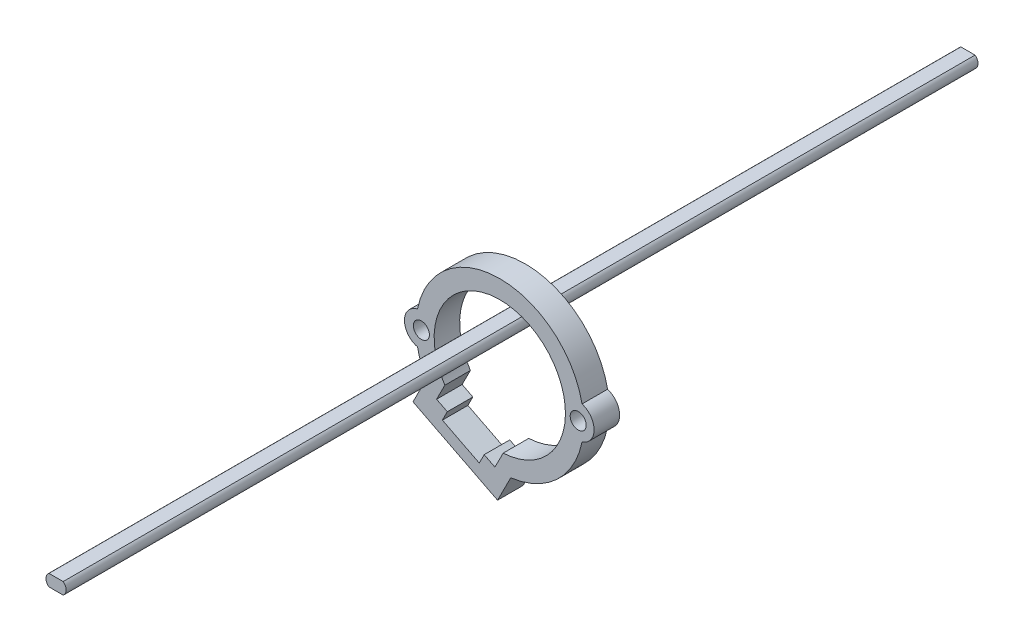
SolidWorks part; units mm, degrees
ref_plane "Front Plane" through (0, 0, 0) normal (0, 0, 1) x (1, 0, 0)
ref_plane "Top Plane" through (0, 0, 0) normal (0, 1, 0) x (1, 0, 0)
ref_plane "Right Plane" through (0, 0, 0) normal (1, 0, 0) x (0, 0, -1)
sketch "Sketch1" plane through (0, 0, 0) normal (0, 0, 1) x (1, 0, 0)
  circle A0 centre (0, 0) radius 23
  circle A1 centre (0, 0) radius 18
  dimension "D1" = 36
  dimension "D2" = 5
extrude "Boss-Extrude1" add sketch "Sketch1" along normal blind 7
sketch "Sketch3" plane through (0, 0, 0) normal (0, 0, 1) x (1, 0, 0)
  line L0 (-23.8014, -18.1679) -> (-0.6174, -29.9366)
  line L1 (-0.6174, -29.9366) -> (3.0037, -22.803)
  line L2 (-23.8014, -18.1679) -> (-20.1803, -11.0343)
  circle A0 centre (0, 0) radius 23 construction
  arc A2 (-20.1803, -11.0343) -> (3.0037, -22.803) centre (0, 0) ccw
  dimension "D1" = 26
  dimension "D2" = 8
  dimension "D3" = 8
extrude "Boss-Extrude2" add sketch "Sketch3" along normal blind 7
sketch "Sketch5" plane through (0, 0, 0) normal (0, 0, 1) x (1, 0, 0)
  line L0 (-15.0623, -9.8553) -> (-17.3255, -14.3138)
  line L1 (-17.3255, -14.3138) -> (-1.3285, -22.4342)
  line L2 (-1.3285, -22.4342) -> (0.9347, -17.9757)
  line L4 (-23.8014, -18.1679) -> (-0.6174, -29.9366) construction
  circle A0 centre (0, 0) radius 18 construction
  arc A1 (0.9347, -17.9757) -> (-15.0623, -9.8553) centre (0, 0) cw
  dimension "D1" = 17.94
  dimension "D2" = 5
  dimension "D3" = 5
extrude "Cut-Extrude1" cut sketch "Sketch5" along normal blind 7
sketch "Sketch6" plane through (0, 0, 0) normal (0, 0, 1) x (1, 0, 0)
  arc A0 (-22.5555, -4.5) -> (-22.5555, 4.5) centre (-21.5191, 0) cw
  circle A1 centre (0, 0) radius 23 construction
  arc A2 (22.5555, -4.5) -> (22.5555, 4.5) centre (21.1441, 0) ccw
  arc A3 (-22.5555, -4.5) -> (-22.5555, 4.5) centre (0, 0) cw
  arc A4 (22.5555, -4.5) -> (22.5555, 4.5) centre (0, 0) ccw
  dimension "D1" = 4.5
  dimension "D2" = 4.5
  dimension "D3" = 4.5
  dimension "D4" = 4.5
extrude "Boss-Extrude3" add sketch "Sketch6" along normal blind 7
sketch "Sketch7" plane through (0, 0, 0) normal (0, 0, 1) x (1, 0, 0)
  circle A0 centre (-21.5, 0) radius 2.2
  circle A1 centre (21.5, 0) radius 2.2
  dimension "D1" = 4.4
  dimension "D2" = 21.5
  dimension "D3" = 21.5
extrude "Cut-Extrude2" cut sketch "Sketch7" along normal blind 7
sketch "Sketch8" plane through (0, 0, 0) normal (0, 0, 1) x (1, 0, 0)
  line L0 (-14.3829, -15.8075) -> (-4.2711, -20.9405)
  line L1 (-17.3255, -14.3138) -> (-1.3285, -22.4342) construction
  line L2 (-4.2711, -20.9405) -> (-5.629, -23.6155)
  line L3 (-5.629, -23.6155) -> (-15.7408, -18.4826)
  line L4 (-15.7408, -18.4826) -> (-14.3829, -15.8075)
  line L5 (-15.0623, -9.8553) -> (-17.3255, -14.3138) construction
  line L6 (-1.3285, -22.4342) -> (0.9347, -17.9757) construction
  dimension "D1" = 3
  dimension "D2" = 3
  dimension "D3" = 3.3
  dimension "D4" = 3.3
extrude "Cut-Extrude3" cut sketch "Sketch8" along normal blind 7
sketch "Sketch9" plane through (0, 0, 0) normal (0, 0, 1) x (1, 0, 0)
  line L0 (-5.6, 9.21) -> (-1.7, 9.21)
  line L1 (-1.7, 5.99) -> (-5.6, 5.99)
  arc A3 (-5.6, 9.21) -> (-5.6, 5.99) centre (-4.4135, 7.6) ccw
  arc A4 (-1.7, 9.21) -> (-1.7, 5.99) centre (-2.8865, 7.6) cw
  dimension "D4" = 2
  dimension "D7" = 2
  dimension "D1" = 5.99
  dimension "D2" = 1.7
  dimension "D3" = 3.9
  dimension "D5" = 3.22
  dimension "D6" = 1.7
extrude "Boss-Extrude4" add sketch "Sketch9" along normal mid plane 250 separate body
